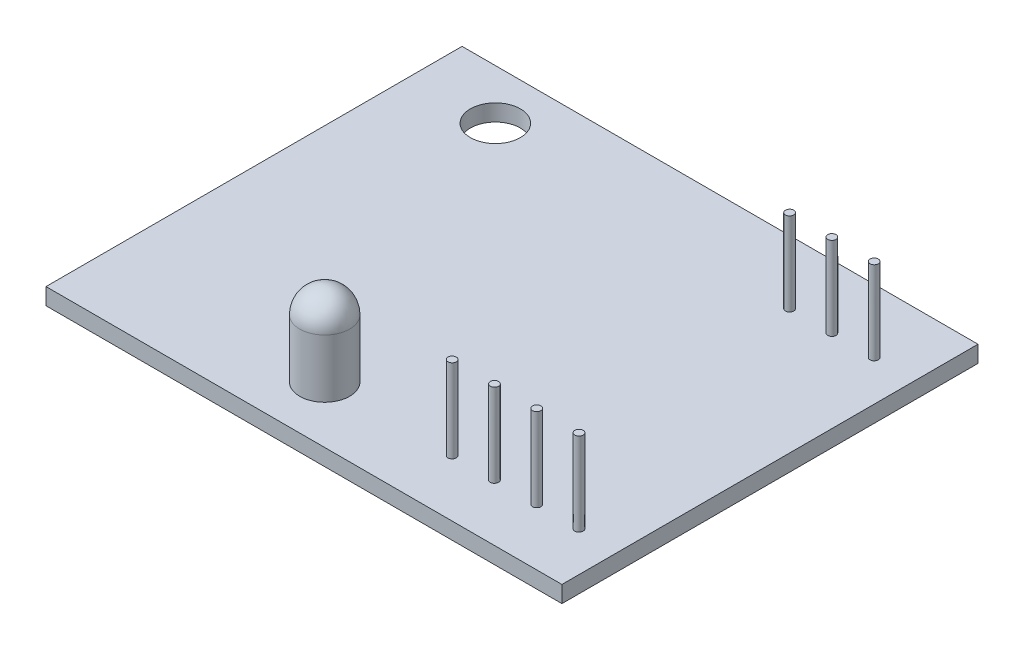
SolidWorks part; units mm, degrees
ref_plane "Přední rovina" through (0, 0, 0) normal (0, 0, 1) x (1, 0, 0)
ref_plane "Horní rovina" through (0, 0, 0) normal (0, 1, 0) x (1, 0, 0)
ref_plane "Pravá rovina" through (0, 0, 0) normal (1, 0, 0) x (0, 0, -1)
sketch "Skica1" plane through (0, 0, 0) normal (0, 1, 0) x (1, 0, 0)
  line L1 (0, 0) -> (31, 0)
  line L2 (0, 0) -> (0, 25)
  line L3 (0, 25) -> (31, 25)
  line L4 (31, 0) -> (31, 25)
  dimension "D1" = 25
  dimension "D2" = 31
extrude "Přidat vysunutím1" add sketch "Skica1" along normal blind 1
sketch "Skica2" plane through (0, 0, 0) normal (0, -1, 0) x (1, 0, 0)
  line L0 (1.5, -6.5) -> (1.5, -9.75)
  line L1 (1.5, -9.75) -> (2, -9.75)
  line L2 (2, -9.75) -> (2, -10.25)
  line L3 (2, -10.25) -> (1.5, -10.25)
  line L4 (1.5, -10.25) -> (1.5, -13.5)
  line L5 (1.5, -13.5) -> (8.5, -13.5)
  line L6 (8.5, -13.5) -> (8.5, -10.25)
  line L7 (8.5, -10.25) -> (8, -10.25)
  line L8 (8, -10.25) -> (8, -9.75)
  line L9 (8, -9.75) -> (8.5, -9.75)
  line L10 (8.5, -9.75) -> (8.5, -6.5)
  line L11 (8.5, -6.5) -> (1.5, -6.5)
  line L12 (0, -25) -> (0, 0) construction
  line L13 (1.5, -6.5) -> (8.5, -13.5) construction
  line L14 (31, -25) -> (0, -25) construction
  point P12 (5, -10)
  dimension "D1" = 7
  dimension "D2" = 7
  dimension "D3" = 0.5
  dimension "D4" = 5
  dimension "D5" = 15
extrude "Přidat vysunutím2" add sketch "Skica2" along normal blind 6 separate body
sketch "Skica3" plane through (0, -6, 0) normal (0, -1, 0) x (1, 0, 0)
  line L0 (1.5, -13.5) -> (8.5, -13.5) construction
  line L1 (1.5, -10.25) -> (1.5, -13.5) construction
  line L12 (8.5, -6.5) -> (1.5, -6.5) construction
  line L13 (2.5, -7.5) -> (7.5, -7.5)
  line L14 (2.5, -7.5) -> (2.5, -12.5)
  line L15 (2.5, -12.5) -> (7.5, -12.5)
  line L16 (7.5, -7.5) -> (7.5, -12.5)
  line L17 (8.5, -13.5) -> (8.5, -10.25) construction
  dimension "D1" = 1
  dimension "D2" = 1
  dimension "D3" = 1
  dimension "D4" = 1
extrude "Odebrat vysunutím1" cut sketch "Skica3" against normal blind 0.5
sketch "Skica4" plane through (0, 0, 0) normal (0, -1, 0) x (1, 0, 0)
  line L0 (0, -25) -> (0, 0) construction
  line L1 (31, -25) -> (0, -25) construction
  circle A0 centre (5, -22) radius 1.5
  dimension "D1" = 5
  dimension "D2" = 3
  dimension "D3" = 3
extrude "Odebrat vysunutím2" cut sketch "Skica4" against normal through all
chamfer "Zkosení1" distance 0.3 angle 45 6 edges at (8.5, -6, -11.875) (5, -6, -13.5) (1.5, -6, -11.875) (8.5, -6, -8.125) (5, -6, -6.5) (1.5, -6, -8.125)
sketch "Skica5" plane through (0, 1, 0) normal (0, 1, 0) x (1, 0, 0)
  line L0 (20.995, 3.41) -> (23.535, 3.41) construction
  line L1 (23.535, 3.41) -> (26.075, 3.41) construction
  line L3 (26.075, 3.41) -> (28.615, 3.41) construction
  line L4 (28.57, 21.19) -> (26.03, 21.19) construction
  line L5 (26.03, 21.19) -> (23.49, 21.19) construction
  line L6 (0, 25) -> (0, 0) construction
  line L7 (31, 25) -> (0, 25) construction
  circle A0 centre (20.995, 3.41) radius 0.25
  circle A1 centre (23.535, 3.41) radius 0.25
  circle A2 centre (26.075, 3.41) radius 0.25
  circle A3 centre (28.615, 3.41) radius 0.25
  circle A4 centre (28.57, 21.19) radius 0.25
  circle A5 centre (26.03, 21.19) radius 0.25
  circle A6 centre (23.49, 21.19) radius 0.25
  dimension "D2" = 0.5
  dimension "D4" = 3.81
  dimension "D5" = 20.995
  dimension "D6" = 21.59
  dimension "D1" = 2.54
  dimension "D3" = 28.57
extrude "Přidat vysunutím3" add sketch "Skica5" along normal blind 5 separate body
sketch "Skica7" plane through (0, 1, 0) normal (0, 1, 0) x (1, 0, 0)
  circle A0 centre (28.615, 3.41) radius 0.25 construction
  circle A1 centre (26.075, 3.41) radius 0.25 construction
  circle A2 centre (23.535, 3.41) radius 0.25 construction
  circle A3 centre (20.995, 3.41) radius 0.25 construction
  circle A4 centre (28.57, 21.19) radius 0.25 construction
  circle A5 centre (26.03, 21.19) radius 0.25 construction
  circle A6 centre (23.49, 21.19) radius 0.25 construction
  circle A21 centre (23.49, 21.19) radius 0.25
  circle A22 centre (26.03, 21.19) radius 0.25
  circle A23 centre (28.57, 21.19) radius 0.25
  circle A24 centre (20.995, 3.41) radius 0.25
  circle A25 centre (23.535, 3.41) radius 0.25
  circle A26 centre (26.075, 3.41) radius 0.25
  circle A27 centre (28.615, 3.41) radius 0.25
extrude "Přidat vysunutím5" add sketch "Skica7" along normal blind 0.5
sketch "Skica6" plane through (0, 1, 0) normal (0, 1, 0) x (1, 0, 0)
  line L0 (0, 25) -> (0, 0) construction
  line L1 (31, 25) -> (0, 25) construction
  circle A0 centre (13.335, 3.41) radius 1.5
  dimension "D1" = 13.335
  dimension "D2" = 21.59
  dimension "D3" = 3
extrude "Přidat vysunutím4" add sketch "Skica6" along normal blind 5
fillet "Zaoblit1" radius 1.5 1 edges at (13.335, 6, -1.91)
